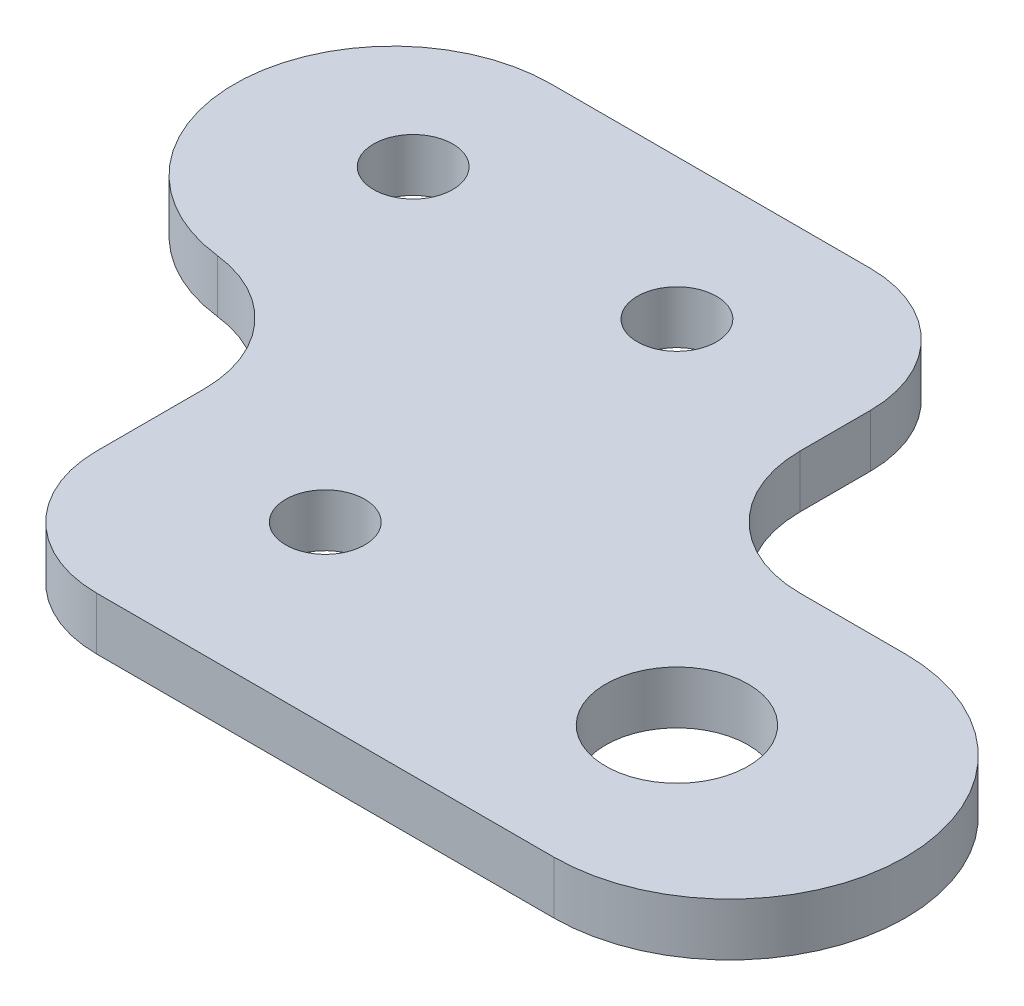
SolidWorks part; units mm, degrees
ref_plane "Alzado" through (0, 0, 0) normal (0, 0, 1) x (1, 0, 0)
ref_plane "Planta" through (0, 0, 0) normal (0, 1, 0) x (1, 0, 0)
ref_plane "Vista lateral" through (0, 0, 0) normal (1, 0, 0) x (0, 0, -1)
ref_plane "Plano1" through (0, -1.5001, 0) normal (0, 1, 0) x (1, 0, 0)
sketch "Croquis1" plane through (0, -1.5001, 0) normal (0, 1, 0) x (1, 0, 0)
  line L0 (-14, -9.8938) -> (-14, -16)
  line L1 (-7, -23) -> (19, -23)
  line L2 (19, -3) -> (13, -3)
  line L3 (6, 4) -> (6, 8)
  line L4 (-1, 15) -> (-19.16, 15)
  circle A0 centre (16, -13) radius 4.05
  circle A1 centre (-19, 7) radius 2.25
  circle A2 centre (-4, -13) radius 2.25
  circle A3 centre (-4, 7) radius 2.25
  arc A4 (-20.195, -2.9403) -> (-14, -9.8938) centre (-21, -9.8938) cw
  arc A5 (-14, -16) -> (-7, -23) centre (-7, -16) ccw
  arc A6 (19, -23) -> (19, -3) centre (19, -13) ccw
  arc A7 (13, -3) -> (6, 4) centre (13, 4) cw
  arc A8 (6, 8) -> (-1, 15) centre (-1, 8) ccw
  arc A9 (-19.16, 15) -> (-20.195, -2.9403) centre (-19.16, 6) ccw
extrude "Saliente-Extruir1" add sketch "Croquis1" against normal blind 3
